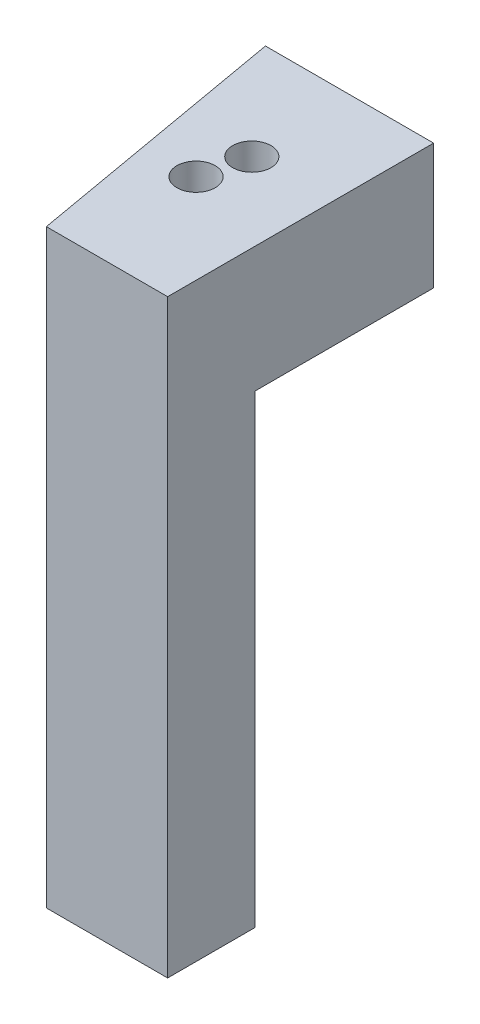
SolidWorks part; units mm, degrees
ref_plane "Front" through (0, 0, 0) normal (0, 0, 1) x (1, 0, 0)
ref_plane "Top" through (0, 0, 0) normal (0, 1, 0) x (1, 0, 0)
ref_plane "Right" through (0, 0, 0) normal (1, 0, 0) x (0, 0, -1)
sketch "Sketch1" plane through (0, 0, 0) normal (0, 1, 0) x (1, 0, 0)
  line L0 (0, 0) -> (-4.4787, 25.4)
  line L1 (0, 0) -> (10, 0)
  line L5 (-4.4787, 25.4) -> (10, 25.4)
  line L6 (10, 25.4) -> (10, 0)
  dimension "D1" = 100
  dimension "D2" = 25.4
  dimension "D3" = 10
extrude "Boss-Extrude1" add sketch "Sketch1" along normal blind 50.8
sketch "Sketch2" plane through (0, 0, 0) normal (0, -1, 0) x (1, 0, 0)
  line L0 (10, -25.4) -> (-4.4787, -25.4)
  line L1 (-4.4787, -25.4) -> (-1.7633, -10)
  line L2 (-4.4787, -25.4) -> (0, 0) construction
  line L3 (-1.7633, -10) -> (10, -10)
  line L4 (10, 0) -> (10, -25.4) construction
  line L5 (10, -10) -> (10, -25.4)
  line L6 (0, 0) -> (10, 0) construction
  dimension "D1" = 10
extrude "Cut-Extrude1" cut sketch "Sketch2" against normal blind 40
sketch "Sketch3" plane through (0, 0, 0) normal (0, -1, 0) x (-1, 0, 0)
  line L0 (-10, 2.5) -> (0.4408, 2.5)
  line L1 (-10, 0) -> (-10, 10) construction
  line L2 (1.7633, 10) -> (0, 0) construction
  line L3 (0, 0) -> (-10, 0) construction
  line L4 (-10, 2.5) -> (-10, 0)
  line L5 (-10, 0) -> (0, 0)
  line L6 (0, 0) -> (0.4408, 2.5)
  dimension "D1" = 2.5
extrude "Cut-Extrude2" cut sketch "Sketch3" against normal blind 50.8
sketch "Sketch4" plane through (0, 40, 0) normal (0, -1, 0) x (-1, 0, 0)
  line L0 (-10, 16.5649) -> (-3.1821, 16.5649)
  line L1 (-10, 25.4) -> (-10, 10) construction
  line L2 (0.4408, 2.5) -> (-10, 2.5) construction
  line L3 (-3.1821, 16.5649) -> (-2.2781, 12.6683)
  circle A0 centre (-3.1821, 16.5649) radius 1.65
  circle A1 centre (-2.2781, 12.6683) radius 1.65
  dimension "D1" = 6.8179
  dimension "D2" = 14.0649
  dimension "D3" = 4
  dimension "D4" = 3.8965
extrude "Cut-Extrude3" cut sketch "Sketch4" against normal blind 25.4
